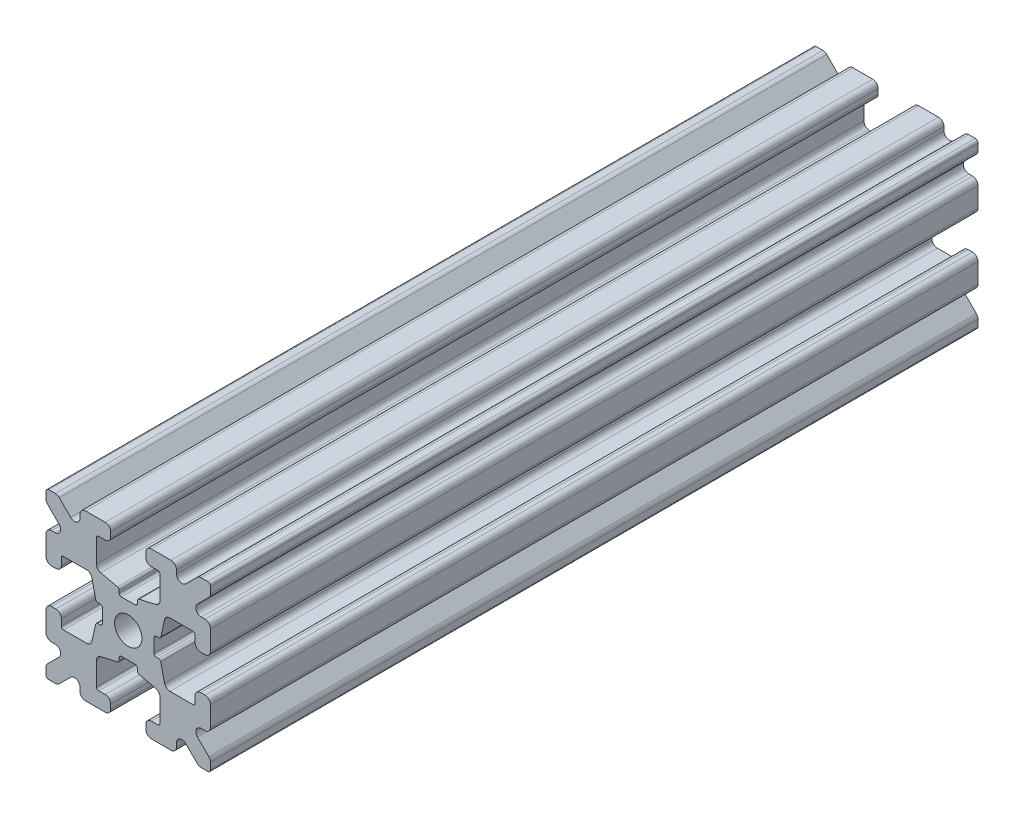
SolidWorks part; units mm, degrees
ref_plane "Front Plane" through (0, 0, 0) normal (0, 0, 1) x (1, 0, 0)
ref_plane "Top Plane" through (0, 0, 0) normal (0, 1, 0) x (1, 0, 0)
ref_plane "Right Plane" through (0, 0, 0) normal (1, 0, 0) x (0, 0, -1)
sketch "Sketch1" plane through (0, 0, 0) normal (0, 0, 1) x (1, 0, 0)
  line L1 (-7.5, -7.5) -> (7.5, -7.5)
  line L2 (-7.5, -7.5) -> (-7.5, 7.5)
  line L3 (-7.5, 7.5) -> (7.5, 7.5)
  line L4 (7.5, -7.5) -> (7.5, 7.5)
  line L5 (-7.5, -7.5) -> (7.5, 7.5) construction
  line L6 (-7.5, 7.5) -> (7.5, -7.5) construction
  circle A0 centre (0, 0) radius 1.25
  point P0 (0, 0)
  dimension "D2" = 2.5
  dimension "D1" = 15
extrude "Boss-Extrude1" add sketch "Sketch1" along normal mid plane 70
fillet "Fillet1" radius 0.25 4 edges at (7.5, -7.5, 0) (-7.5, -7.5, 0) (7.5, 7.5, 0) (-7.5, 7.5, 0)
sketch "Sketch2" plane through (0, 0, 35) normal (0, 0, 1) x (1, 0, 0)
  line L0 (-7.5, 7.25) -> (-7.5, -7.25) construction
  line L1 (-7.5, 1.6) -> (-6.1, 1.6)
  line L2 (-7.5, 1.6) -> (-7.5, -1.6)
  line L3 (-7.5, -1.6) -> (-6.1, -1.6)
  line L4 (-6.1, 1.6) -> (-6.1, 2.9)
  line L5 (0, 0) -> (-12.1036, 0) construction
  line L6 (-6.1, -2.9) -> (-3.4, -2.9)
  line L7 (0, 0) -> (-7.25, 7.25) construction
  line L8 (-6.1, 2.9) -> (-3.4, 2.9)
  line L9 (-3.4, -2.9) -> (-3.4, 2.9)
  line L10 (55, 0) -> (-55, 0) construction
  line L11 (-6.1, -2.9) -> (-6.1, -1.6)
  line L12 (2.9, 6.1) -> (1.6, 6.1)
  line L13 (2.9, 3.4) -> (-2.9, 3.4)
  line L14 (-2.9, 6.1) -> (-2.9, 3.4)
  line L15 (2.9, 6.1) -> (2.9, 3.4)
  line L16 (-1.6, 6.1) -> (-2.9, 6.1)
  line L17 (1.6, 7.5) -> (1.6, 6.1)
  line L18 (-1.6, 7.5) -> (1.6, 7.5)
  line L19 (-1.6, 7.5) -> (-1.6, 6.1)
  line L20 (-1.6, -7.5) -> (-1.6, -6.1)
  line L21 (-1.6, -7.5) -> (1.6, -7.5)
  line L22 (1.6, -7.5) -> (1.6, -6.1)
  line L23 (-1.6, -6.1) -> (-2.9, -6.1)
  line L24 (2.9, -6.1) -> (2.9, -3.4)
  line L25 (-2.9, -6.1) -> (-2.9, -3.4)
  line L26 (2.9, -3.4) -> (-2.9, -3.4)
  line L27 (2.9, -6.1) -> (1.6, -6.1)
  line L28 (6.1, -2.9) -> (6.1, -1.6)
  line L29 (3.4, -2.9) -> (3.4, 2.9)
  line L30 (6.1, 2.9) -> (3.4, 2.9)
  line L31 (6.1, -2.9) -> (3.4, -2.9)
  line L32 (6.1, 1.6) -> (6.1, 2.9)
  line L33 (7.5, -1.6) -> (6.1, -1.6)
  line L34 (7.5, 1.6) -> (7.5, -1.6)
  line L35 (7.5, 1.6) -> (6.1, 1.6)
  dimension "D1" = 3.2
  dimension "D2" = 5.8
  dimension "D3" = 1.4
  dimension "D4" = 2.7
extrude "Cut-Extrude1" cut sketch "Sketch2" against normal through all
sketch "Sketch4" plane through (0, 0, 35) normal (0, 0, 1) x (1, 0, 0)
  line L0 (-3.4, 2.9) -> (-2.75, 0)
  line L1 (55, 0) -> (-55, 0) construction
  line L2 (-2.75, 0) -> (-3.4, -2.9)
  line L3 (-3.4, -2.9) -> (-3.4, 2.9) construction
  line L4 (-3.4, 2.9) -> (-3.4, -2.9)
  line L5 (-2.9, 3.4) -> (0, 2.75)
  line L6 (0, 2.75) -> (2.9, 3.4)
  line L7 (2.9, 3.4) -> (-2.9, 3.4)
  line L8 (3.4, 2.9) -> (2.75, 0)
  line L9 (2.75, 0) -> (3.4, -2.9)
  line L10 (3.4, -2.9) -> (3.4, 2.9)
  line L11 (-2.9, -3.4) -> (0, -2.75)
  line L12 (0, -2.75) -> (2.9, -3.4)
  line L13 (2.9, -3.4) -> (-2.9, -3.4)
  circle A2 centre (0, 0) radius 2.75
  circle A3 centre (0, 0) radius 2.75 construction
  dimension "D1" = 1.5
extrude "Cut-Extrude3" cut sketch "Sketch4" against normal through all
fillet "Fillet3" radius 0.5 16 edges at (-6.1, -1.6, 0) (-7.5, -1.6, 0) (-6.1, 1.6, 0) (-7.5, 1.6, 0) (-1.6, -7.5, 0) (-1.6, -6.1, 0) (1.6, -7.5, 0) (1.6, -6.1, 0) (6.1, -1.6, 0) (7.5, -1.6, 0) (7.5, 1.6, 0) (6.1, 1.6, 0) (1.6, 7.5, 0) (1.6, 6.1, 0) (-1.6, 7.5, 0) (-1.6, 6.1, 0)
fillet "Fillet4" radius 0.5 8 edges at (-3.4, 2.9, 0) (-3.4, -2.9, 0) (2.9, -3.4, 0) (-2.9, -3.4, 0) (3.4, -2.9, 0) (3.4, 2.9, 0) (-2.9, 3.4, 0) (2.9, 3.4, 0)
fillet "Fillet5" radius 3 4 edges at (0, -2.75, 0) (2.75, 0, 0) (-2.75, 0, 0) (0, 2.75, 0)
fillet "Fillet6" radius 0.2 8 edges at (-2.9, -6.1, 0) (2.9, -6.1, 0) (6.1, -2.9, 0) (6.1, 2.9, 0) (2.9, 6.1, 0) (-2.9, 6.1, 0) (-6.1, -2.9, 0) (-6.1, 2.9, 0)
sketch "Sketch5" plane through (0, 0, 35) normal (0, 0, 1) x (1, 0, 0)
  line L0 (0, 0) -> (-7.25, 7.25) construction
  line L1 (-7.5, 6.4393) -> (-5.4607, 4.4)
  line L2 (-6.4393, 7.5) -> (-4.4, 5.4607)
  line L3 (-7.5, 4.4) -> (-5.4607, 4.4)
  line L4 (-3.8003, 2.9) -> (-5.9, 2.9) construction
  line L5 (0, 0) -> (-12.1819, 0) construction
  line L6 (-4.4, 7.5) -> (-4.4, 5.4607)
  line L7 (-2.9, 5.9) -> (-2.9, 3.8003) construction
  line L8 (-7.5, 6.4393) -> (-7.5, 4.4)
  line L9 (-7.5, 7.25) -> (-7.5, 2.1) construction
  line L10 (2.1, -7.5) -> (7.25, -7.5) construction
  line L11 (7.5, -7.25) -> (7.5, -2.1) construction
  line L12 (7.25, 7.5) -> (2.1, 7.5) construction
  line L13 (-2.1, 7.5) -> (-7.25, 7.5) construction
  line L14 (-4.4, 7.5) -> (-6.4393, 7.5)
  line L16 (55, 0) -> (-55, 0) construction
  line L17 (0, 0) -> (0, 10.993) construction
  line L18 (0, -54.6431) -> (0, 54.6431) construction
  line L20 (4.4, 7.5) -> (6.4393, 7.5)
  line L22 (7.5, 6.4393) -> (7.5, 4.4)
  line L23 (4.4, 7.5) -> (4.4, 5.4607)
  line L24 (7.5, 4.4) -> (5.4607, 4.4)
  line L25 (6.4393, 7.5) -> (4.4, 5.4607)
  line L26 (7.5, 6.4393) -> (5.4607, 4.4)
  line L27 (7.5, -6.4393) -> (5.4607, -4.4)
  line L28 (6.4393, -7.5) -> (4.4, -5.4607)
  line L29 (7.5, -4.4) -> (5.4607, -4.4)
  line L30 (4.4, -7.5) -> (4.4, -5.4607)
  line L31 (7.5, -6.4393) -> (7.5, -4.4)
  line L33 (4.4, -7.5) -> (6.4393, -7.5)
  line L36 (-4.4, -7.5) -> (-6.4393, -7.5)
  line L38 (-7.5, -6.4393) -> (-7.5, -4.4)
  line L39 (-4.4, -7.5) -> (-4.4, -5.4607)
  line L40 (-7.5, -4.4) -> (-5.4607, -4.4)
  line L41 (-6.4393, -7.5) -> (-4.4, -5.4607)
  line L42 (-7.5, -6.4393) -> (-5.4607, -4.4)
  dimension "D1" = 1.5
  dimension "D2" = 1.5
  dimension "D3" = 1.5
extrude "Cut-Extrude4" cut sketch "Sketch5" against normal through all
fillet "Fillet8" radius 0.5 24 edges at (-5.4607, 4.4, 0) (-7.5, 4.4, 0) (-5.4607, -4.4, 0) (-7.5, -4.4, 0) (-4.4, -7.5, 0) (-4.4, -5.4607, 0) (4.4, -7.5, 0) (4.4, -5.4607, 0) (5.4607, -4.4, 0) (7.5, -4.4, 0) (7.5, 4.4, 0) (5.4607, 4.4, 0) (4.4, 5.4607, 0) (4.4, 7.5, 0) (-4.4, 5.4607, 0) (-4.4, 7.5, 0) (-6.4393, 7.5, 0) (-7.5, 6.4393, 0) (6.4393, 7.5, 0) (7.5, 6.4393, 0) (6.4393, -7.5, 0) (7.5, -6.4393, 0) (-6.4393, -7.5, 0) (-7.5, -6.4393, 0)
sketch "Sketch6" plane through (0, 0, 35) normal (0, 0, 1) x (1, 0, 0)
  line L0 (0, 0) -> (0, 11.013) construction
  line L1 (0.6561, 2.8971) -> (2.1235, 2.8971) construction
  line L2 (0, -54.6431) -> (0, 54.6431) construction
  line L3 (0, 0) -> (7.25, 7.25) construction
  line L4 (7.5, 0.8255) -> (7.5, -0.8255)
  line L5 (2.3471, 0.8255) -> (7.5, 0.8255)
  line L6 (0, 0) -> (12.4016, 0) construction
  line L7 (0.8255, -7.5) -> (-0.8255, -7.5)
  line L8 (2.3471, -0.8255) -> (2.3471, 0.8255)
  line L9 (0.8255, -2.3471) -> (0.8255, -7.5)
  line L10 (7.5, -0.8255) -> (2.3471, -0.8255)
  line L11 (-7.5, -0.8255) -> (-2.3471, -0.8255)
  line L12 (-2.3471, -0.8255) -> (-2.3471, 0.8255)
  line L13 (-0.8255, -2.3471) -> (0.8255, -2.3471)
  line L14 (-0.8255, 7.5) -> (-0.8255, 2.3471)
  line L15 (-0.8255, 2.3471) -> (0.8255, 2.3471)
  line L16 (-0.8255, -7.5) -> (-0.8255, -2.3471)
  line L17 (0.8255, 2.3471) -> (0.8255, 7.5)
  line L18 (0.8255, 7.5) -> (-0.8255, 7.5)
  line L19 (3.9, 7.5) -> (2.1, 7.5) construction
  line L20 (-2.3471, 0.8255) -> (-7.5, 0.8255)
  line L21 (-7.5, 0.8255) -> (-7.5, -0.8255)
  point P5 (0, -2.5973)
  point P7 (0, 2.5973)
  dimension "D3" = 0.55
  dimension "D1" = 1.651
extrude "Cut-Extrude5" cut sketch "Sketch6" against normal through all
fillet "Fillet10" radius 0.2 16 edges at (-2.935, 0.8255, 0) (-2.935, -0.8255, 0) (2.935, -0.8255, 0) (2.935, 0.8255, 0) (0.8255, 2.935, 0) (-0.8255, 2.935, 0) (-2.3471, 0.8255, 0) (-2.3471, -0.8255, 0) (0.8255, 2.3471, 0) (-0.8255, 2.3471, 0) (2.3471, 0.8255, 0) (2.3471, -0.8255, 0) (0.8255, -2.935, 0) (0.8255, -2.3471, 0) (-0.8255, -2.3471, 0) (-0.8255, -2.935, 0)
